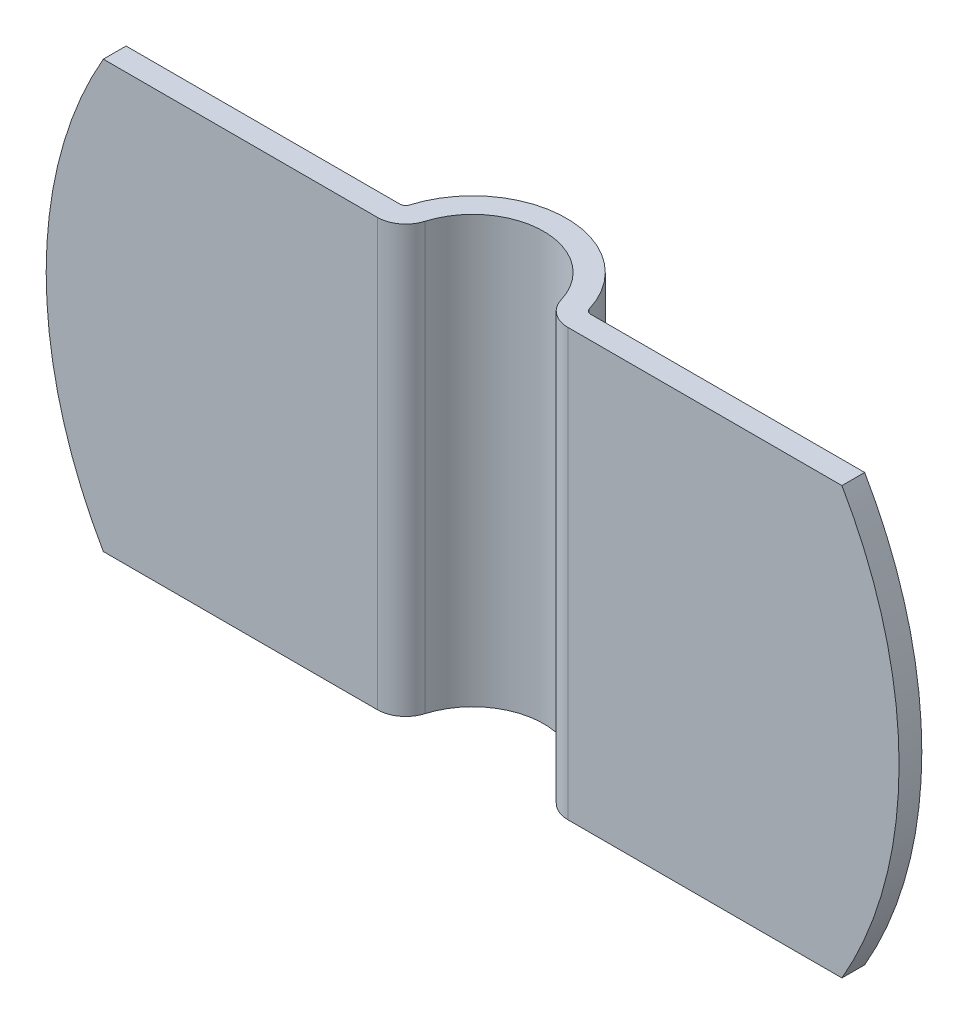
SolidWorks part; units mm, degrees
material "Chrome Stainless Steel"
ref_plane "Front Plane" through (0, 0, 0) normal (0, 0, 1) x (1, 0, 0)
ref_plane "Top Plane" through (0, 0, 0) normal (0, 1, 0) x (1, 0, 0)
ref_plane "Right Plane" through (0, 0, 0) normal (1, 0, 0) x (0, 0, -1)
sketch "Sketch1" plane through (0, 0, 0) normal (0, 1, 0) x (1, 0, 0)
  line L0 (-3, 0) -> (-0.6708, 0)
  line L1 (-55, 0) -> (55, 0) construction
  line L2 (0.6708, 0) -> (3, 0)
  line L3 (0, -55) -> (0, 55) construction
  circle A0 centre (0, 0) radius 0.5 construction
  arc A1 (-0.4792, 0.1429) -> (0.4792, 0.1429) centre (0, 0) cw
  arc A2 (-0.6708, 0) -> (-0.4792, 0.1429) centre (-0.6708, 0.2) ccw
  arc A3 (0.6708, 0) -> (0.4792, 0.1429) centre (0.6708, 0.2) cw
  point P12 (-0.5, 0)
  point P15 (0.5, 0)
  dimension "D1" = 1
  dimension "D2" = 0.2
  dimension "D3" = 3
  dimension "D4" = 6
extrude "Extrude-Thin1" add sketch "Sketch1" along normal blind 3 thin thin type one direction reverse wall 0.16
sketch "Sketch2" plane through (0, 0, 0) normal (0, 0, 1) x (1, 0, 0)
  line L0 (0, -0.55) -> (0, 0.55) construction
  line L1 (0.55, 0) -> (-0.55, 0) construction
  circle A0 centre (0, 1.5) radius 3
  dimension "D2" = 6
  dimension "D1" = 1.5
extrude "Extrude2" cut sketch "Sketch2" against normal through all flip side to cut
